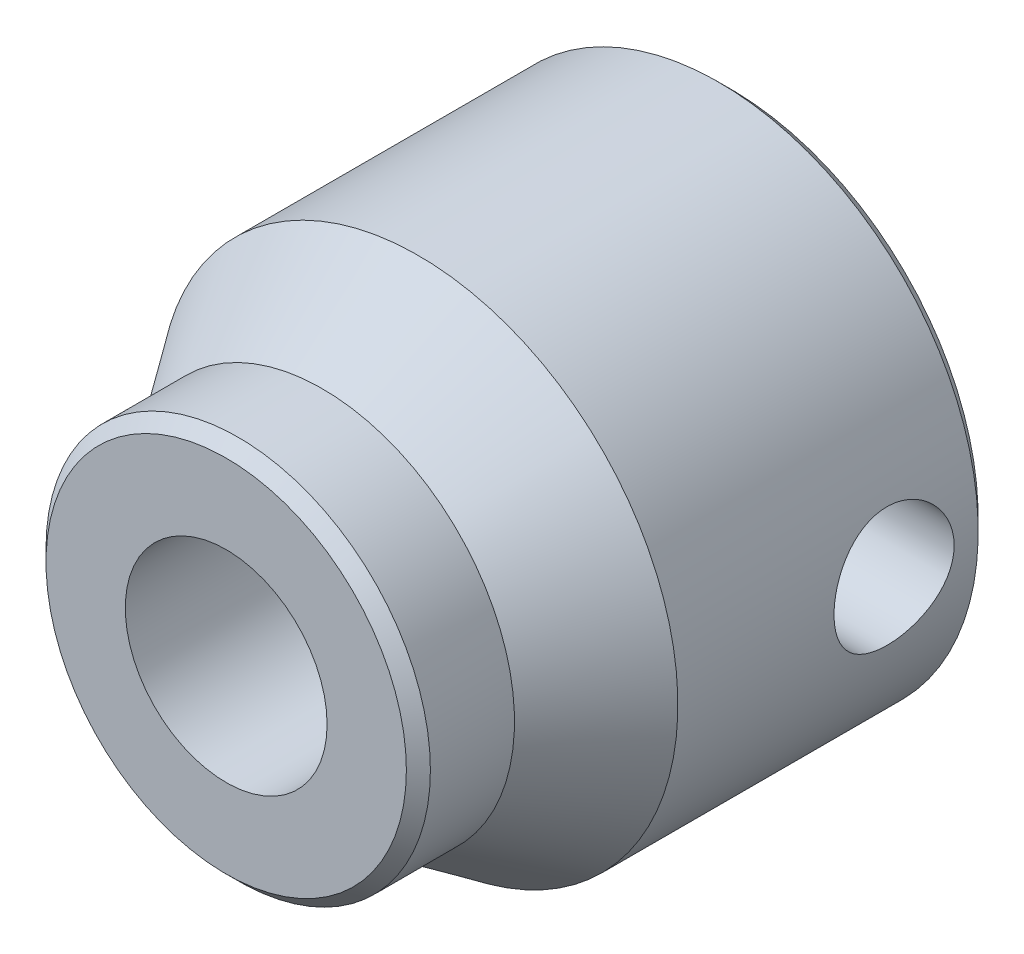
SolidWorks part; units mm, degrees
ref_plane "Top" through (0, 0, 0) normal (0, 0, 1) x (1, 0, 0)
ref_plane "Front" through (0, 0, 0) normal (0, 1, 0) x (1, 0, 0)
ref_plane "Right" through (0, 0, 0) normal (1, 0, 0) x (0, 0, -1)
ref_plane "Base Tangent Plane" through (5.4, 0, 0) normal (1, 0, 0) x (0, 0, -1)
sketch "Body Sketch" plane through (0, 0, 0) normal (0, 1, 0) x (-1, 0, 0)
  line L1 (1, 10.5) -> (4, 10.5)
  line L2 (4, 10.5) -> (4, 8.5)
  line L3 (4, 8.5) -> (5.4, 6.5)
  line L4 (5.4, 6.5) -> (5.4, 0)
  line L5 (5.4, 0) -> (2.5, 0)
  line L8 (0, 0) -> (0, 10.5) construction
  line L9 (1, 10.5) -> (1, 6)
  line L10 (1, 6) -> (2.5, 6)
  line L11 (2.5, 6) -> (2.5, 0)
  dimension "D1" = 6.5
  dimension "D4" = 5.4
  dimension "D5" = 2.5
  dimension "D7" = 1
  dimension "D8" = 6
  dimension "D2" = 4.5
  dimension "D6" = 2
  dimension "D3" = 4
  dimension "D9" = 1.5
revolve "Body Revolve" add sketch "Body Sketch" angle 360 about L8
hole_wizard "Connector M5x0.8 Tapped Hole" positions "Connector Position Sketch" profile "Sketch5" tap size "M5x0.8" standard "ANSI Metric"
sketch "Connector Position Sketch" plane through (0, 0, 10.5) normal (0, 0, 1) x (1, 0, 0)
  point P0 (0, 0)
cosmetic thread "Connector Hole Thread" parameters "D1"=5, "D2"=5
sketch "Sketch5" plane through (0, 0, 10.5) normal (1, 0, 0) x (0, -1, 0)
  line L0 (0, 0) -> (0, 8.6618)
  line L1 (0, 8.6618) -> (2.1, 7.4)
  line L2 (2.1, 7.4) -> (2.1, 0)
  line L5 (2.1, 0) -> (0, 0)
  line L10 (0, 8.6618) -> (-2.1, 7.4) construction
  line L11 (0, -6.35) -> (0, 107.95) construction
  dimension "Tap Drill Dia." = 4.2
  dimension "Tap Drill Depth" = 7.4
  dimension "Drill Angle" = 118
hole_wizard "Set Screw 1 M3x0.5 Tapped Hole" positions "Set Screw Position Sketch" profile "Set Screw Profile Sketch" tap size "M3x0.5" standard "ANSI Metric"
sketch3d "Set Screw Position Sketch"
  point P0 (5.4, 0, 2)
  dimension "D1" = 2
sketch "Set Screw Profile Sketch" plane through (5.4, 0, 2) normal (0, 1, 0) x (0, 0, -1)
  line L0 (0, 0) -> (0, 2.9)
  line L1 (0, 2.9) -> (1.25, 2.9)
  line L2 (1.25, 2.9) -> (1.25, 0)
  line L5 (1.25, 0) -> (0, 0)
  line L11 (0, -6.35) -> (0, 107.95) construction
  dimension "Thru Tap Drill Dia." = 2.5
  dimension "Thru Tap Drill Depth" = 2.9
cosmetic thread "Set Screw 1 Hole Thread" parameters "D2"=3
chamfer "Edge Chamfers" distance 0.25 angle 45 2 edges at (-5.4, 0, 0) (-4, 0, 10.5)
equation "\"Base Diameter\"= 10.8"
equation "\"D4@Body Sketch\"=\"Base Diameter\"/2"
equation "\"D1@Base Tangent Plane\"=\"Base Diameter\"/2"
